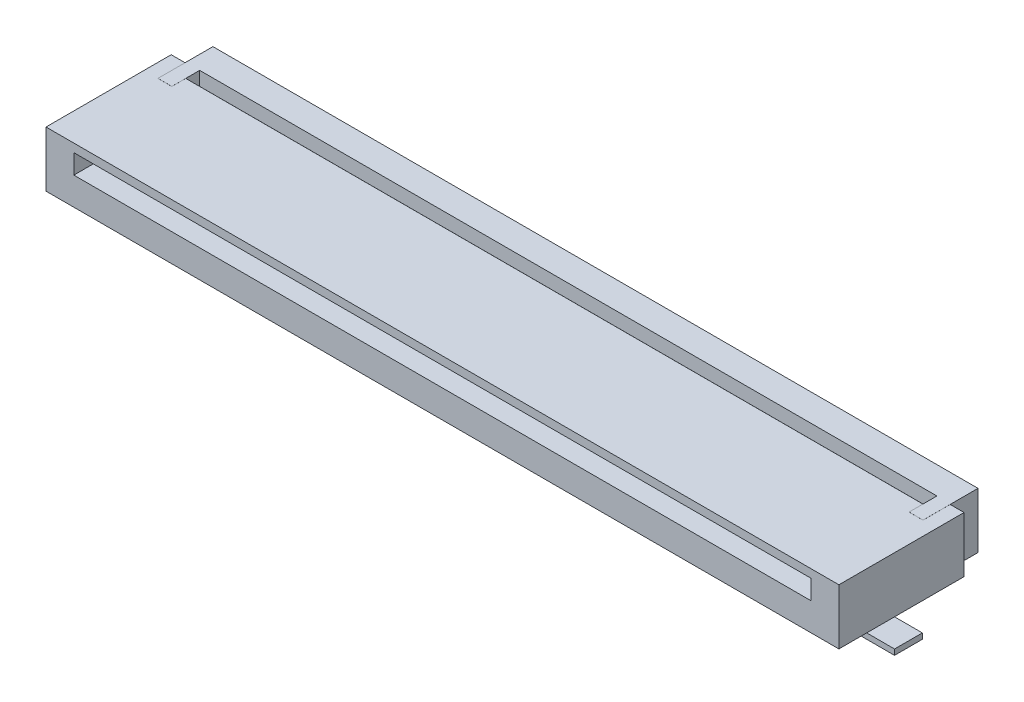
SolidWorks part; units mm, degrees
ref_plane "前视基准面" through (0, 0, 0) normal (0, 0, 1) x (1, 0, 0)
ref_plane "上视基准面" through (0, 0, 0) normal (0, 1, 0) x (1, 0, 0)
ref_plane "右视基准面" through (0, 0, 0) normal (1, 0, 0) x (0, 0, -1)
sketch "草图1" plane through (0, 0, 0) normal (0, 1, 0) x (1, 0, 0)
  line L1 (-14.25, -2.75) -> (14.25, -2.75)
  line L2 (-14.25, -2.75) -> (-14.25, 2.75)
  line L3 (-14.25, 2.75) -> (14.25, 2.75)
  line L4 (14.25, -2.75) -> (14.25, 2.75)
  line L5 (-14.25, -2.75) -> (14.25, 2.75) construction
  line L6 (-14.25, 2.75) -> (14.25, -2.75) construction
  point P0 (0, 0)
  dimension "D1" = 28.5
  dimension "D2" = 5.5
extrude "凸台-拉伸1" add sketch "草图1" along normal blind 2
sketch "草图2" plane through (0, 2, 0) normal (0, 1, 0) x (1, 0, 0)
  line L0 (0, -6.1376) -> (0, 6.1376) construction
  line L1 (-14.25, 2.75) -> (-13.75, 2.75)
  line L2 (-14.25, 2.75) -> (-14.25, 1.75)
  line L3 (-14.25, 1.75) -> (-13.75, 1.75)
  line L4 (-13.75, 2.75) -> (-13.75, 1.75)
  line L5 (13.75, 2.75) -> (13.75, 1.75)
  line L6 (14.25, 1.75) -> (13.75, 1.75)
  line L7 (14.25, 2.75) -> (14.25, 1.75)
  line L8 (14.25, 2.75) -> (13.75, 2.75)
  point P9 (0, 0)
  dimension "D1" = 1
  dimension "D2" = 0.5
extrude "切除-拉伸1" cut sketch "草图2" against normal through all
sketch "草图4" plane through (0, 0, 0) normal (0, -1, 0) x (1, 0, 0)
  line L0 (-14.25, -1.75) -> (-14.25, 2.75) construction
  line L1 (-15.25, 1.75) -> (-13.25, 1.75)
  line L2 (-15.25, 1.75) -> (-15.25, 0.75)
  line L3 (-15.25, 0.75) -> (-13.25, 0.75)
  line L4 (-13.25, 1.75) -> (-13.25, 0.75)
  line L5 (-14.25, 2.75) -> (14.25, 2.75) construction
  line L6 (0, 0) -> (0, 7.0534) construction
  line L7 (13.25, 1.75) -> (13.25, 0.75)
  line L8 (15.25, 0.75) -> (13.25, 0.75)
  line L9 (15.25, 1.75) -> (15.25, 0.75)
  line L10 (15.25, 1.75) -> (13.25, 1.75)
  dimension "D1" = 1
  dimension "D2" = 2
  dimension "D3" = 1
  dimension "D4" = 1
extrude "凸台-拉伸2" add sketch "草图4" along normal blind 0.2
sketch "草图5" plane through (0, 0, 0) normal (0, -1, 0) x (1, 0, 0)
  line L0 (13.75, -2.75) -> (13.75, -1.75) construction
  line L1 (13.25, -2.55) -> (-13.25, -2.55)
  line L2 (13.25, -2.55) -> (13.25, -2.35)
  line L3 (13.25, -2.35) -> (-13.25, -2.35)
  line L4 (-13.25, -2.55) -> (-13.25, -2.35)
  line L5 (-13.75, -1.75) -> (-13.75, -2.75) construction
  line L6 (13.75, -2.75) -> (-13.75, -2.75) construction
  dimension "D1" = 0.5
  dimension "D2" = 0.5
  dimension "D3" = 0.2
  dimension "D4" = 0.2
extrude "凸台-拉伸3" add sketch "草图5" along normal blind 0.3
sketch "草图6" plane through (0, 0, 2.75) normal (0, 0, 1) x (1, 0, 0)
  line L0 (-14.25, 2) -> (14.25, 2) construction
  line L1 (-13.25, 1.7) -> (13.25, 1.7)
  line L2 (-13.25, 1.7) -> (-13.25, 1)
  line L3 (-13.25, 1) -> (13.25, 1)
  line L4 (13.25, 1.7) -> (13.25, 1)
  line L5 (-14.25, 2) -> (-14.25, 0) construction
  line L6 (14.25, 2) -> (14.25, 0) construction
  dimension "D1" = 0.3
  dimension "D2" = 1
  dimension "D3" = 1
  dimension "D4" = 0.7
extrude "切除-拉伸2" cut sketch "草图6" against normal blind 4.5
sketch "草图7" plane through (0, 2, 0) normal (0, 1, 0) x (1, 0, 0)
  line L0 (-13.75, 1.75) -> (-13.75, 0.7733)
  line L1 (-13.75, 0.7733) -> (-13.25, 0.7733)
  line L2 (-13.25, 0.7733) -> (-13.25, 1.2733)
  line L3 (-13.25, 1.2733) -> (13.25, 1.2733)
  line L4 (-13.75, 1.75) -> (-14.25, 1.75)
  line L5 (-14.25, 1.75) -> (-14.25, -2.75)
  line L6 (-14.25, -2.75) -> (14.25, -2.75)
  line L7 (-14.25, -2.75) -> (14.25, -2.75) construction
  line L8 (0, 0) -> (0, 7.5114) construction
  line L9 (14.25, 1.75) -> (14.25, -2.75)
  line L10 (13.75, 1.75) -> (14.25, 1.75)
  line L11 (13.25, 0.7733) -> (13.25, 1.2733)
  line L12 (13.75, 0.7733) -> (13.25, 0.7733)
  line L13 (13.75, 1.75) -> (13.75, 0.7733)
  point P19 (0, -2.75)
  point P22 (0, 1.2733)
  dimension "D1" = 0.5
  dimension "D2" = 0.5
extrude "切除-拉伸3" cut sketch "草图7" against normal blind 0.002
sketch "草图8" plane through (0, 2, 0) normal (0, 1, 0) x (1, 0, 0)
  line L0 (13.25, 0.7733) -> (13.25, 1.2733) construction
  line L1 (-13.25, 1.2733) -> (13.25, 1.2733)
  line L2 (-13.25, 1.2733) -> (-13.25, 1.7733)
  line L3 (-13.25, 1.7733) -> (13.25, 1.7733)
  line L4 (13.25, 1.2733) -> (13.25, 1.7733)
  line L5 (-13.25, 1.2733) -> (-13.25, 0.7733) construction
  dimension "D1" = 0.5
extrude "切除-拉伸4" cut sketch "草图8" against normal blind 0.5
